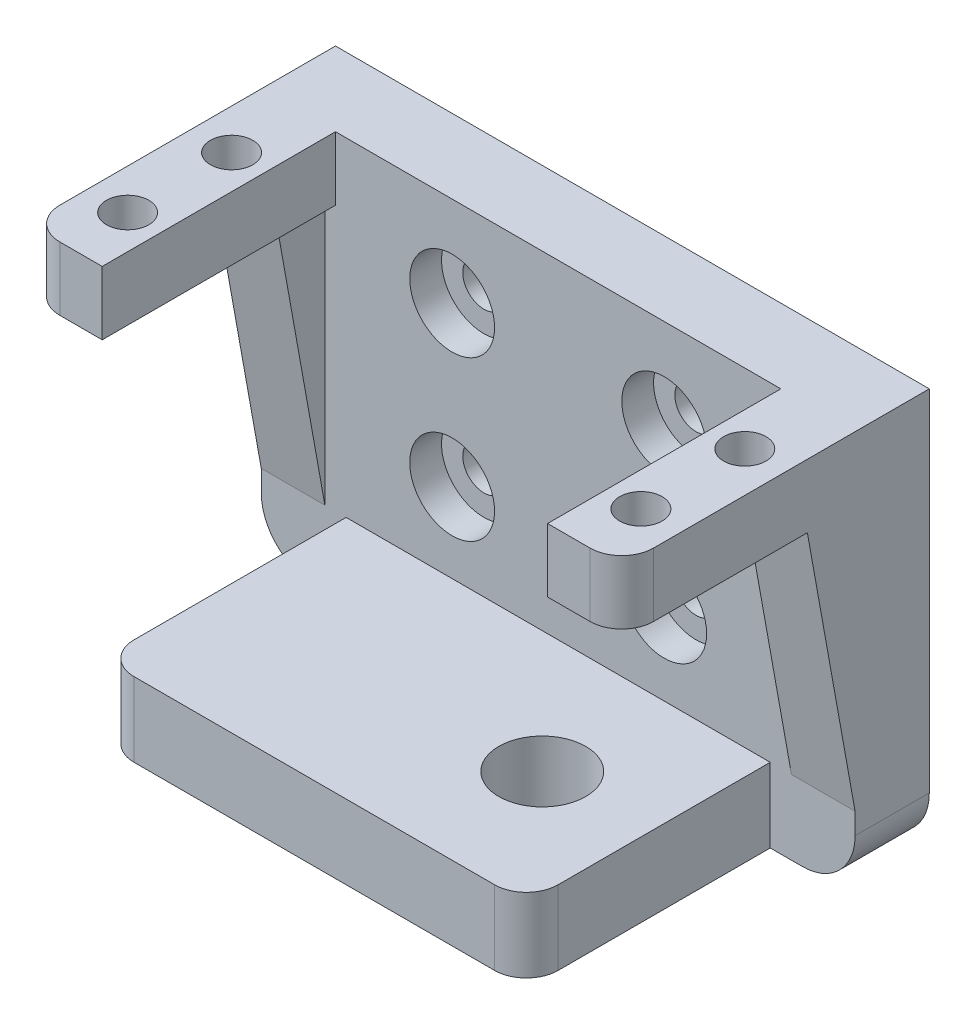
SolidWorks part; units mm, degrees
ref_plane "前视基准面" through (0, 0, 0) normal (0, 0, 1) x (1, 0, 0)
ref_plane "上视基准面" through (0, 0, 0) normal (0, 1, 0) x (1, 0, 0)
ref_plane "右视基准面" through (0, 0, 0) normal (1, 0, 0) x (0, 0, -1)
sketch "草图4" plane through (0, 0, 0) normal (0, 1, 0) x (1, 0, 0)
  line L0 (0, 17.6534) -> (0, -5.833) construction
  line L1 (-24.2, 14.9) -> (-24.2, 5.1) construction
  line L2 (-28, 28.5) -> (28, 28.5)
  line L3 (-28, 28.5) -> (-28, 2.5)
  line L4 (-25, -0.5) -> (-21, -0.5)
  line L5 (28, 28.5) -> (28, 2.5)
  line L6 (-28, 28.5) -> (28, -0.5) construction
  line L7 (-28, -0.5) -> (28, 28.5) construction
  line L8 (-21, 21.5) -> (21, 21.5)
  line L9 (-21, 21.5) -> (-21, -0.5)
  line L11 (21, 21.5) -> (21, -0.5)
  line L12 (-21, 21.5) -> (21, -0.5) construction
  line L13 (-21, -0.5) -> (21, 21.5) construction
  line L14 (21, -0.5) -> (25, -0.5)
  line L16 (24.2, 14.9) -> (24.2, 5.1) construction
  circle A0 centre (-24.2, 14.9) radius 2
  circle A1 centre (-24.2, 5.1) radius 2
  circle A2 centre (24.2, 14.9) radius 2
  circle A3 centre (24.2, 5.1) radius 2
  arc A4 (25, -0.5) -> (28, 2.5) centre (25, 2.5) ccw
  arc A5 (-25, -0.5) -> (-28, 2.5) centre (-25, 2.5) cw
  point P3 (0, 14)
  point P8 (0, 10.5)
  dimension "D6" = 4
  dimension "D7" = 4
  dimension "D8" = 4
  dimension "D9" = 4
  dimension "D10" = 3
  dimension "D1" = 22
  dimension "D3" = 7
  dimension "D4" = 42
  dimension "D5" = 7
  dimension "D11" = 24.2
  dimension "D12" = 9.8
  dimension "D13" = 24.2
  dimension "D14" = 9.8
extrude "凸台-拉伸1" add sketch "草图4" against normal blind 6 from surface
sketch "草图5" plane through (0, 0, -28.5) normal (0, 0, -1) x (-1, 0, 0)
  line L0 (0, 4.5795) -> (0, 37.3232) construction
  line L1 (-28, 74.5) -> (28, 74.5) construction
  line L2 (-20, 74.5) -> (20, 74.5)
  line L3 (-20, 74.5) -> (-20, 42.5)
  line L4 (-20, 42.5) -> (20, 42.5)
  line L5 (20, 74.5) -> (20, 42.5)
  line L6 (-20, 74.5) -> (20, 42.5) construction
  line L7 (-20, 42.5) -> (20, 74.5) construction
  line L8 (-20, 64.5) -> (20, 64.5) construction
  circle A0 centre (-10, 72) radius 2
  circle A1 centre (10, 72) radius 2
  circle A4 centre (10, 57) radius 2
  circle A5 centre (-10, 57) radius 2
  point P3 (0, 58.5)
  dimension "D3" = 4
  dimension "D1" = 40
  dimension "D2" = 32
  dimension "D4" = 20
  dimension "D6" = 10
  dimension "D7" = 15
extrude "凸台-拉伸2" add sketch "草图5" against normal blind 7
sketch "草图6" plane through (0, 0, 0) normal (0, 0, 1) x (1, 0, 0)
  circle A0 centre (-10, 72) radius 4
  circle A1 centre (10, 72) radius 4
  circle A5 centre (-10, 57) radius 4
  circle A6 centre (10, 57) radius 4
  dimension "D1" = 8
extrude "切除-拉伸1" cut sketch "草图6" against normal blind 3 from surface at -21.5 starting at face at (0, 68, -21.5)
sketch "草图7" plane through (0, 0, 0) normal (0, 1, 0) x (1, 0, 0)
  line L0 (-20, 21.5) -> (-20, 28.5) construction
  line L1 (20, 21.5) -> (-20, 21.5)
  line L2 (20, 21.5) -> (20, 1.5)
  line L3 (17, -1.5) -> (-17, -1.5)
  line L4 (-20, 21.5) -> (-20, 1.5)
  circle A0 centre (10, 10) radius 4.1
  arc A1 (-17, -1.5) -> (-20, 1.5) centre (-17, 1.5) cw
  arc A2 (17, -1.5) -> (20, 1.5) centre (17, 1.5) ccw
  point P14 (20, -1.5)
  dimension "D1" = 8.2
  dimension "D3" = 3
  dimension "D2" = 23
  dimension "D4" = 11.5
  dimension "D5" = 10
extrude "凸台-拉伸3" add sketch "草图7" along normal blind 7 from surface at 42.5 starting at face at (0, 42.5, -25)
sketch "草图8" plane through (0, 42.5, 0) normal (0, -1, 0) x (1, 0, 0)
  circle A0 centre (10, -10) radius 4.9
  dimension "D1" = 9.8
extrude "切除-拉伸2" cut sketch "草图8" against normal blind 0.9
sketch "草图10" plane through (20, 0, 0) normal (1, 0, 0) x (0, 0, -1)
  line L0 (28.5, 49.5) -> (28.5, 74.5)
  line L1 (28.5, 74.5) -> (28.5, 42.5) construction
  line L2 (28.5, 74.5) -> (17, 74.5)
  line L3 (2.5, 74.5) -> (28.5, 74.5) construction
  line L4 (17, 74.5) -> (21.5, 49.5)
  line L5 (21.5, 74.5) -> (21.5, 49.5) construction
  line L6 (21.5, 49.5) -> (28.5, 49.5)
  dimension "D1" = 25
  dimension "D2" = 11.5
extrude "凸台-拉伸4" add sketch "草图10" along normal blind 6 from offset 2
sketch "草图12" plane through (-20, 0, 0) normal (-1, 0, 0) x (0, 0, 1)
  line L2 (-17, 74.5) -> (-21.5, 49.5) construction
  line L3 (-21.5, 49.5) -> (-21.5, 74.5) construction
  line L4 (-21.5, 49.5) -> (-28.5, 49.5)
  line L5 (-28.5, 42.5) -> (-28.5, 74.5) construction
  line L6 (-28.5, 49.5) -> (-28.5, 74.5)
  line L7 (-21.5, 49.5) -> (-17, 74.5)
  line L8 (-17, 74.5) -> (-28.5, 74.5)
extrude "凸台-拉伸5" add sketch "草图12" along normal blind 6 from offset 2
sketch "草图13" plane through (0, 0, -28.5) normal (0, 0, -1) x (-1, 0, 0)
  line L0 (-20, 42.5) -> (20, 42.5) construction
  line L1 (28, 80.5) -> (-28, 80.5)
  line L2 (28, 80.5) -> (28, 47.5)
  line L3 (23, 42.5) -> (-23, 42.5)
  line L4 (-28, 80.5) -> (-28, 47.5)
  line L5 (-28, 49.5) -> (-28, 80.5) construction
  line L6 (0, 0) -> (0, 19.1257) construction
  line L7 (-15, 77.5) -> (15, 77.5)
  line L8 (-15, 77.5) -> (-15, 52.5)
  line L9 (-15, 52.5) -> (15, 52.5)
  line L10 (15, 77.5) -> (15, 52.5)
  line L11 (-15, 77.5) -> (15, 52.5) construction
  line L12 (-15, 52.5) -> (15, 77.5) construction
  arc A0 (-28, 47.5) -> (-23, 42.5) centre (-23, 47.5) ccw
  arc A1 (28, 47.5) -> (23, 42.5) centre (23, 47.5) cw
  point P13 (0, 65)
  dimension "D1" = 5
  dimension "D2" = 30
  dimension "D3" = 25
  dimension "D4" = 3
extrude "凸台-拉伸6" add sketch "草图13" against normal blind 7
